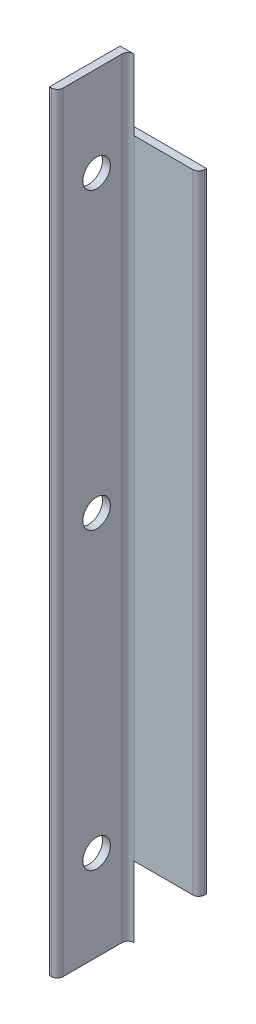
SolidWorks part; units mm, degrees
material "ASTM A36 Steel"
ref_plane "Front Plane" through (0, 0, 0) normal (0, 0, 1) x (1, 0, 0)
ref_plane "Top Plane" through (0, 0, 0) normal (0, 1, 0) x (1, 0, 0)
ref_plane "Right Plane" through (0, 0, 0) normal (1, 0, 0) x (0, 0, -1)
sketch "Sketch1" plane through (0, 0, 0) normal (0, 1, 0) x (1, 0, 0)
  line L0 (-27.4999, 29.2132) -> (-67.4999, 29.2132)
  line L1 (-67.4999, 29.2132) -> (-67.4999, -10.7868)
  line L2 (-67.4999, -10.7868) -> (-66.4999, -10.7868)
  line L3 (-63.4999, -7.7868) -> (-63.4999, 22.2132)
  line L4 (-60.4999, 25.2132) -> (-30.4999, 25.2132)
  line L5 (-27.4999, 28.2132) -> (-27.4999, 29.2132)
  arc A0 (-66.4999, -10.7868) -> (-63.4999, -7.7868) centre (-66.4999, -7.7868) ccw
  arc A1 (-63.4999, 22.2132) -> (-60.4999, 25.2132) centre (-60.4999, 22.2132) cw
  arc A2 (-30.4999, 25.2132) -> (-27.4999, 28.2132) centre (-30.4999, 28.2132) ccw
  point P8 (-63.4999, -10.7868)
  point P13 (-27.4999, 25.2132)
  dimension "D5" = 3
  dimension "D1" = 40
  dimension "D2" = 40
  dimension "D3" = 4
  dimension "D4" = 4
extrude "Boss-Extrude1" add sketch "Sketch1" along normal blind 392
sketch "Sketch2" plane through (-63.4999, 0, 0) normal (1, 0, 0) x (0, 0, -1)
  line L1 (29.2132, 392) -> (25.2132, 392)
  line L2 (29.2132, 392) -> (29.2132, 356)
  line L3 (29.2132, 356) -> (25.2132, 356)
  line L4 (25.2132, 392) -> (25.2132, 356)
  line L5 (29.2132, 392) -> (25.2132, 356) construction
  line L6 (29.2132, 356) -> (25.2132, 392) construction
  line L8 (29.2132, 36) -> (25.2132, 0) construction
  line L9 (29.2132, 0) -> (25.2132, 36) construction
  line L10 (25.2132, 0) -> (25.2132, 36)
  line L11 (29.2132, 36) -> (25.2132, 36)
  line L12 (29.2132, 0) -> (29.2132, 36)
  line L13 (29.2132, 0) -> (25.2132, 0)
  point P4 (27.2132, 374)
  point P14 (27.2132, 18)
  dimension "D1" = 4
  dimension "D2" = 36
extrude "Cut-Extrude1" cut sketch "Sketch2" against normal through all both and the other way through all
sketch "Sketch3" plane through (-63.4999, 0, 0) normal (1, 0, 0) x (0, 0, -1)
  line L0 (-7.7868, 392) -> (-7.7868, 0) construction
  line L1 (-10.7868, 392) -> (-10.7868, 0) construction
  circle A0 centre (9.2132, 196) radius 7
  circle A1 centre (9.2132, 46) radius 7
  circle A2 centre (9.2132, 346) radius 7
  point P8 (-7.7868, 196)
  dimension "D1" = 14
  dimension "D2" = 14
  dimension "D3" = 14
  dimension "D4" = 150
  dimension "D5" = 150
  dimension "D6" = 0
  dimension "D7" = 20
  dimension "D8" = 20
extrude "Cut-Extrude2" cut sketch "Sketch3" against normal blind 10
